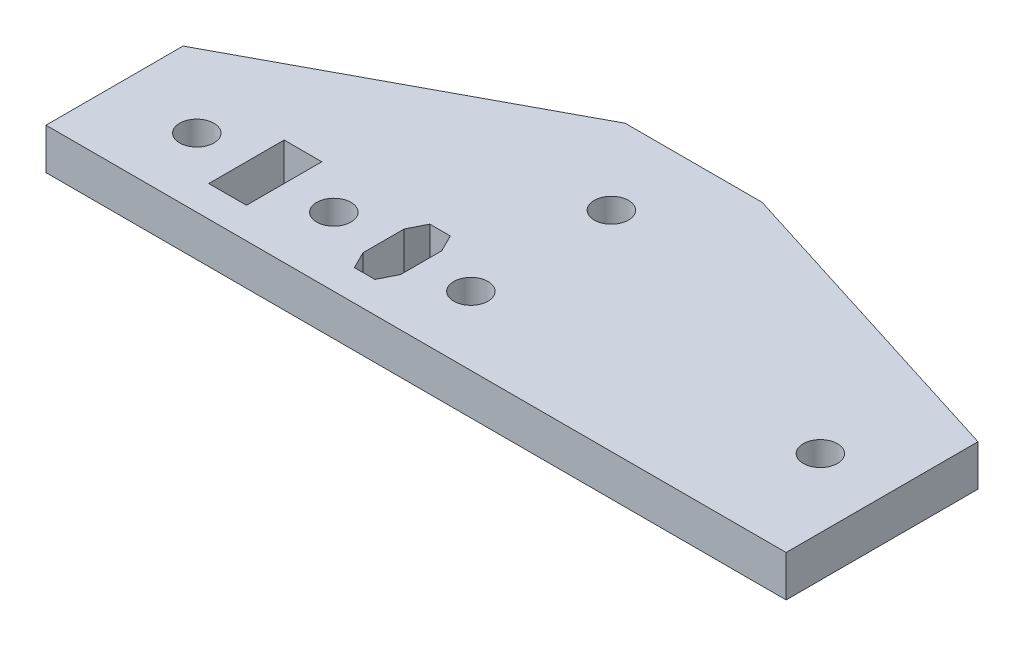
SolidWorks part; units mm, degrees
material "Acrylic (Medium-high impact)"
ref_plane "Front Plane" through (0, 0, 0) normal (0, 0, 1) x (1, 0, 0)
ref_plane "Top Plane" through (0, 0, 0) normal (0, 1, 0) x (1, 0, 0)
ref_plane "Right Plane" through (0, 0, 0) normal (1, 0, 0) x (0, 0, -1)
sketch "Sketch1" plane through (0, 0, 0) normal (0, 1, 0) x (1, 0, 0)
  line L0 (0, 0) -> (0, 20)
  line L1 (0, 20) -> (42, 42.5)
  line L2 (42, 42.5) -> (62, 42.5)
  line L3 (62, 42.5) -> (108, 28)
  line L4 (108, 28) -> (108, 0)
  line L5 (108, 0) -> (0, 0)
  line L7 (19.25, 15.5) -> (24.75, 15.5)
  line L8 (19.25, 15.5) -> (19.25, 4.5)
  line L9 (19.25, 4.5) -> (24.75, 4.5)
  line L10 (24.75, 15.5) -> (24.75, 4.5)
  line L18 (52, 42.5) -> (52, 0) construction
  line L19 (0, 10) -> (108, 10) construction
  line L20 (22, 15.5) -> (22, 4.5) construction
  line L21 (40.5, 15.5) -> (43.5, 15.5)
  line L22 (43.5, 15.5) -> (44.75, 13)
  line L23 (44.75, 13) -> (44.75, 7)
  line L24 (44.75, 7) -> (43.5, 4.5)
  line L25 (43.5, 4.5) -> (40.5, 4.5)
  line L26 (40.5, 4.5) -> (39.25, 7)
  line L27 (39.25, 7) -> (39.25, 13)
  line L28 (39.25, 13) -> (40.5, 15.5)
  line L29 (42, 15.5) -> (42, 4.5) construction
  circle A0 centre (52, 30.5) radius 2.5
  circle A1 centre (52, 10) radius 2.5
  circle A2 centre (32, 10) radius 2.5
  circle A3 centre (12, 10) radius 2.5
  circle A5 centre (98, 15) radius 2.5
  dimension "D1" = 5
  dimension "D2" = 28
  dimension "D3" = 20
  dimension "D4" = 20
  dimension "D5" = 108
  dimension "D6" = 42.5
  dimension "D7" = 11
  dimension "D8" = 5.5
  dimension "D9" = 20
  dimension "D10" = 20
  dimension "D11" = 12
  dimension "D12" = 15
  dimension "D13" = 10
  dimension "D14" = 12
  dimension "D15" = 6
  dimension "D16" = 3
  dimension "D17" = 5.5
  dimension "D18" = 11
extrude "Boss-Extrude1" add sketch "Sketch1" along normal blind 6
